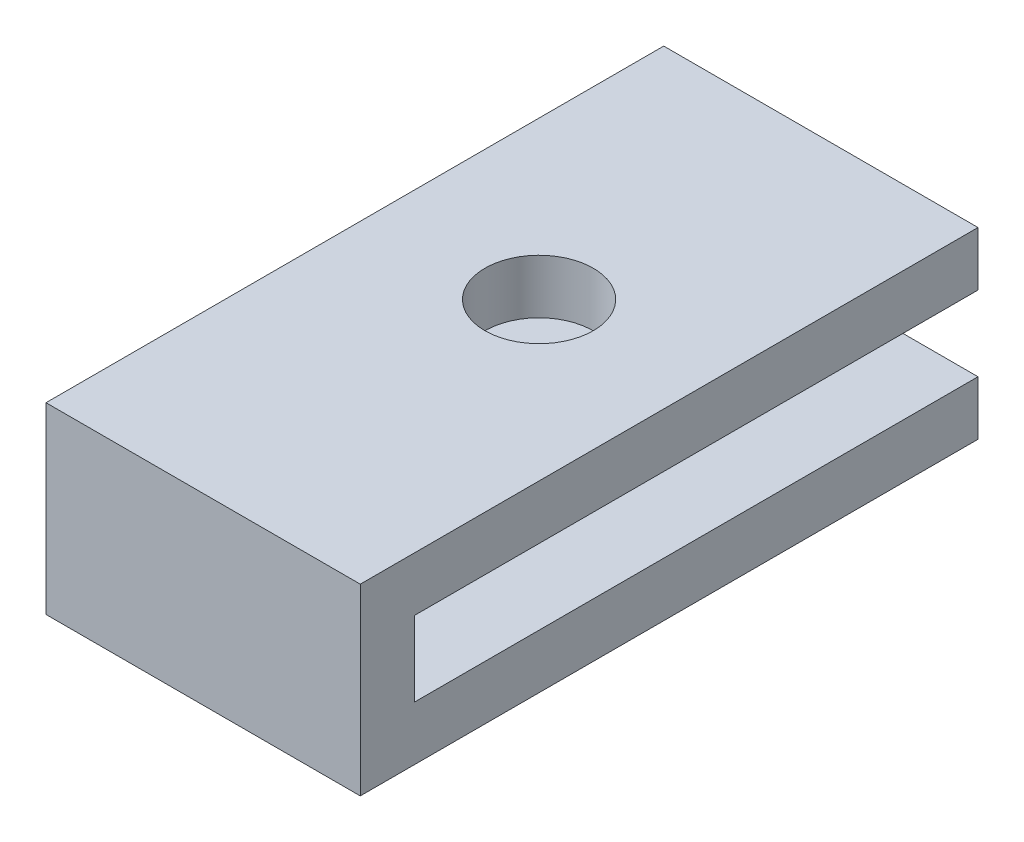
SolidWorks part; units mm, degrees
ref_plane "Front Plane" through (0, 0, 0) normal (0, 0, 1) x (1, 0, 0)
ref_plane "Top Plane" through (0, 0, 0) normal (0, 1, 0) x (1, 0, 0)
ref_plane "Right Plane" through (0, 0, 0) normal (1, 0, 0) x (0, 0, -1)
sketch "Sketch1" plane through (0, 0, 0) normal (0, 1, 0) x (1, 0, 0)
  line L1 (0, 0) -> (14.732, 0)
  line L2 (0, 0) -> (0, 26.416)
  line L3 (0, 26.416) -> (14.732, 26.416)
  line L4 (14.732, 0) -> (14.732, 26.416)
  circle A0 centre (7.366, 13.208) radius 2.54
  dimension "D5" = 5.08
  dimension "D1" = 26.416
  dimension "D2" = 14.732
  dimension "D3" = 13.208
  dimension "D4" = 7.366
extrude "Boss-Extrude1" add sketch "Sketch1" along normal blind 8.5979
sketch "Sketch2" plane through (0, 0, 0) normal (0, 0, 1) x (1, 0, 0)
  line L1 (0, 8.5979) -> (14.732, 8.5979)
  line L2 (0, 8.5979) -> (0, 0)
  line L3 (0, 0) -> (14.732, 0)
  line L4 (14.732, 8.5979) -> (14.732, 0)
extrude "Boss-Extrude2" add sketch "Sketch2" along normal blind 2.54
sketch "Sketch3" plane through (14.732, 0, 0) normal (1, 0, 0) x (0, 0, -1)
  line L0 (26.416, 8.5979) -> (26.416, 0) construction
  line L1 (26.416, 6.0579) -> (0, 6.0579)
  line L2 (26.416, 6.0579) -> (26.416, 2.54)
  line L3 (26.416, 2.54) -> (0, 2.54)
  line L4 (0, 6.0579) -> (0, 2.54)
  line L5 (-2.54, 0) -> (-2.54, 8.5979) construction
  line L6 (-2.54, 8.5979) -> (26.416, 8.5979) construction
  line L7 (-2.54, 0) -> (26.416, 0) construction
  dimension "D1" = 2.54
  dimension "D2" = 2.54
  dimension "D3" = 2.54
extrude "Cut-Extrude1" cut sketch "Sketch3" against normal blind 25.4
